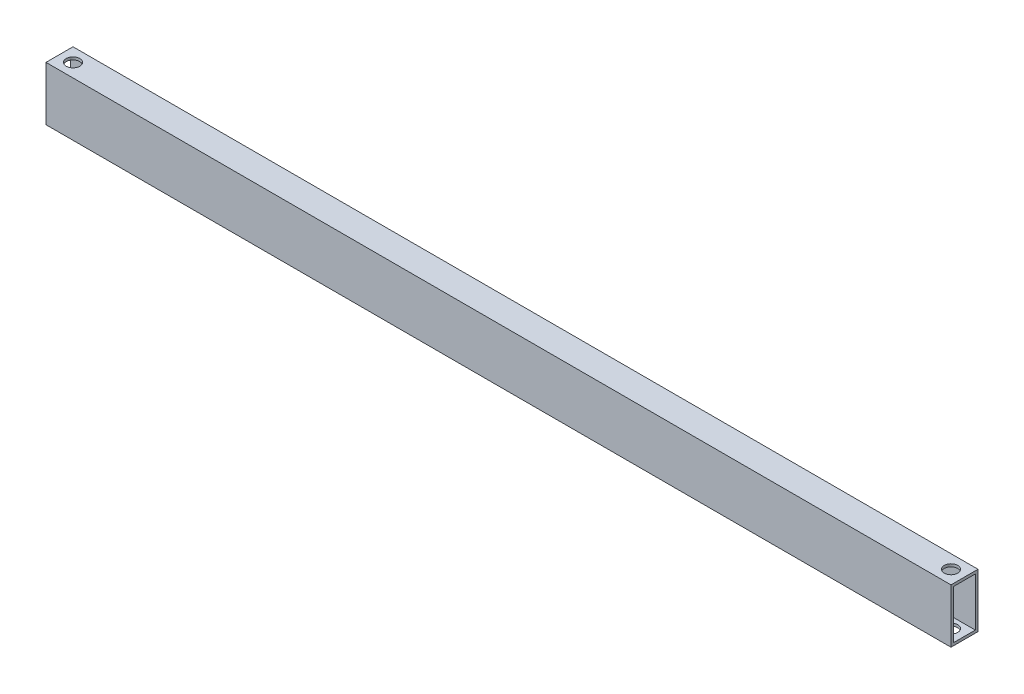
SolidWorks part; units mm, degrees
ref_plane "Front Plane" through (0, 0, 0) normal (0, 0, 1) x (1, 0, 0)
ref_plane "Top Plane" through (0, 0, 0) normal (0, 1, 0) x (1, 0, 0)
ref_plane "Right Plane" through (0, 0, 0) normal (1, 0, 0) x (0, 0, -1)
sketch "Sketch1" plane through (0, 0, 0) normal (1, 0, 0) x (0, 0, -1)
  line L0 (4, -5.0106) -> (4, 12.9894)
  line L1 (5, -6.0106) -> (-5, -6.0106)
  line L2 (5, -6.0106) -> (5, 13.9894)
  line L3 (5, 13.9894) -> (-5, 13.9894)
  line L4 (-5, -6.0106) -> (-5, 13.9894)
  line L5 (5, -6.0106) -> (-5, 13.9894) construction
  line L6 (5, 13.9894) -> (-5, -6.0106) construction
  line L7 (4, 12.9894) -> (-4, 12.9894)
  line L8 (-4, -5.0106) -> (-4, 12.9894)
  line L9 (4, -5.0106) -> (-4, -5.0106)
  point P0 (0, 3.9894)
  dimension "D1" = 10
  dimension "D2" = 20
  dimension "D3" = 1
extrude "Boss-Extrude1" add sketch "Sketch1" along normal blind 225 and the other way blind 110
sketch "Sketch3" plane through (0, 0, -5) normal (0, 0, -1) x (-1, 0, 0)
  line L0 (0, -6.0106) -> (0, 13.9894) construction
  line L1 (110, -6.0106) -> (-225, -6.0106) construction
  line L2 (110, 13.9894) -> (-225, 13.9894) construction
  circle A0 centre (-19.85, 3.9894) radius 2.5
  circle A1 centre (-10, 3.9894) radius 2.5
  circle A2 centre (0, 3.9894) radius 2.5
  circle A3 centre (10, 3.9894) radius 2.5
  circle A4 centre (19.85, 3.9894) radius 2.5
  dimension "D5" = 5
  dimension "D6" = 5
  dimension "D7" = 5
  dimension "D1" = 9.85
  dimension "D2" = 10
  dimension "D3" = 10
  dimension "D8" = 9.85
  dimension "D9" = 10
extrude "Cut-Extrude1" cut sketch "Sketch3" against normal blind 1
sketch "Sketch4" plane through (0, 13.9894, 0) normal (0, 1, 0) x (1, 0, 0)
  line L0 (-110, 5) -> (-110, -5) construction
  line L1 (-110, 5) -> (225, 5) construction
  line L2 (225, 5) -> (225, -5) construction
  circle A0 centre (-105, 0) radius 2.5
  circle A1 centre (220, 0) radius 2.5
  dimension "D1" = 5
  dimension "D4" = 5
  dimension "D2" = 5
  dimension "D3" = 5
  dimension "D5" = 5
  dimension "D6" = 5
extrude "Cut-Extrude2" cut sketch "Sketch4" against normal blind 20
